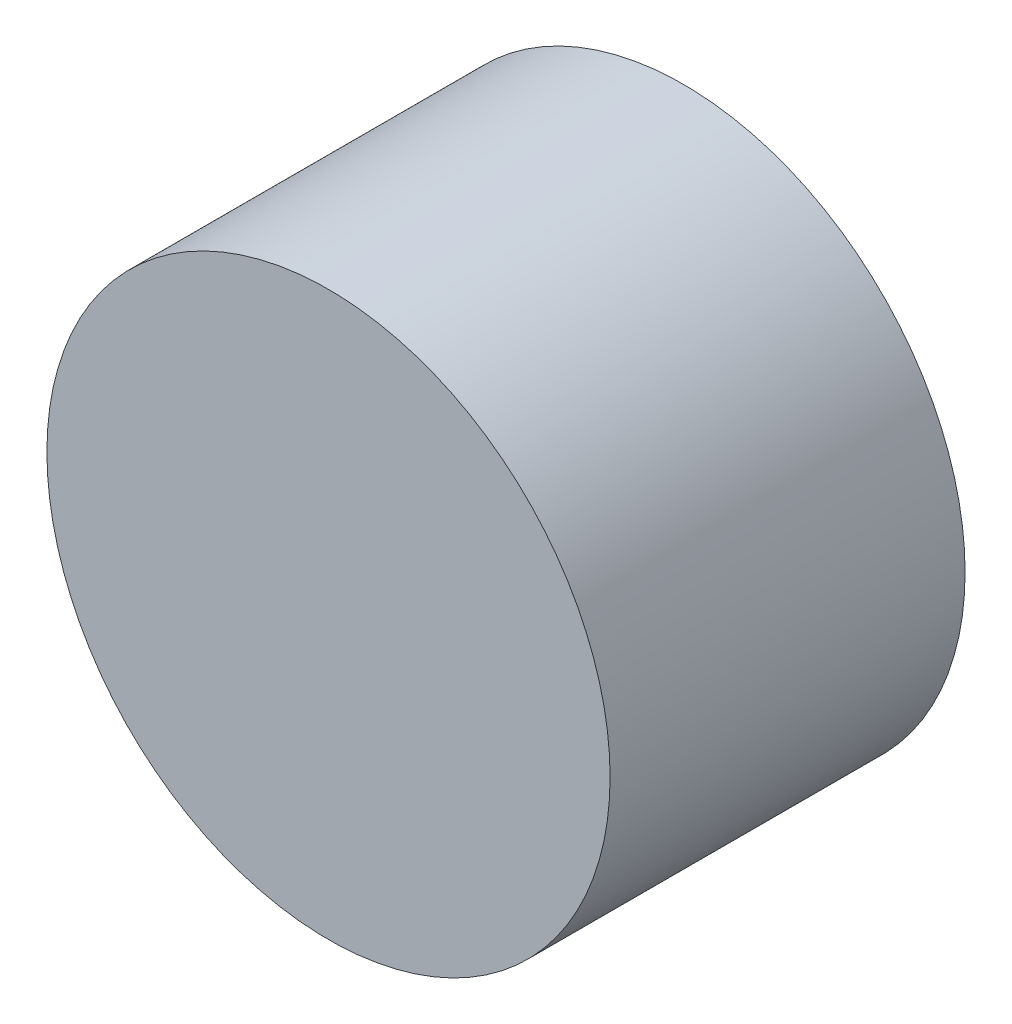
SolidWorks part; units mm, degrees
ref_plane "Спереди" through (0, 0, 0) normal (0, 0, 1) x (1, 0, 0)
ref_plane "Сверху" through (0, 0, 0) normal (0, 1, 0) x (1, 0, 0)
ref_plane "Справа" through (0, 0, 0) normal (1, 0, 0) x (0, 0, -1)
sketch "Эскиз1" plane through (0, 0, 0) normal (0, 0, 1) x (1, 0, 0)
  circle A0 centre (0, 0) radius 23.7976
extrude "Бобышка-Вытянуть1" add sketch "Эскиз1" along normal blind 30
